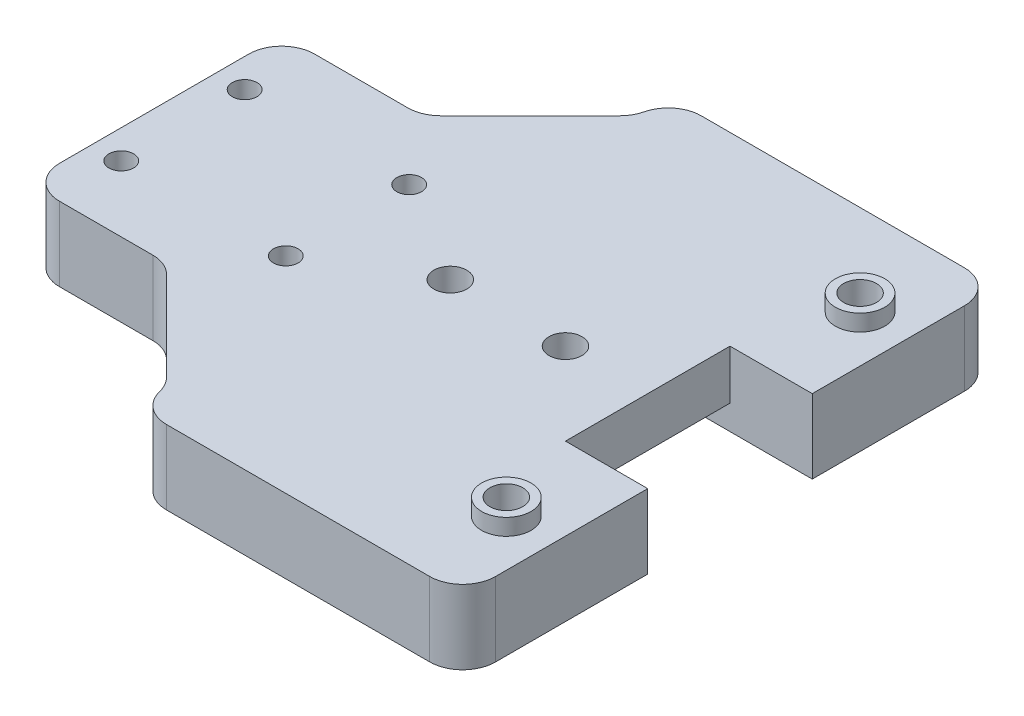
SolidWorks part; units mm, degrees
ref_plane "Front Plane" through (0, 0, 0) normal (0, 0, 1) x (1, 0, 0)
ref_plane "Top Plane" through (0, 0, 0) normal (0, 1, 0) x (1, 0, 0)
ref_plane "Right Plane" through (0, 0, 0) normal (1, 0, 0) x (0, 0, -1)
sketch "Sketch1" plane through (0, 0, 0) normal (0, 1, 0) x (1, 0, 0)
  line L0 (0, 0) -> (21.5, 0) construction
  line L5 (21.5, 20) -> (21.5, -20)
  line L6 (21.5, -20) -> (-20.5, -32.5)
  line L7 (-20.5, -32.5) -> (-84.5, -32.5)
  line L8 (-84.5, -32.5) -> (-84.5, 32.5)
  line L11 (-84.5, 32.5) -> (-20.5, 32.5)
  line L12 (-20.5, 32.5) -> (21.5, 20)
  circle A0 centre (0, 0) radius 12
  point P7 (21.5, 0)
  dimension "D4" = 24
  dimension "D6" = 9.5
  dimension "D1" = 40
  dimension "D2" = 106
  dimension "D3" = 65
  dimension "D5" = 64
extrude "Boss-Extrude1" add sketch "Sketch1" along normal mid plane 9
sketch "Sketch2" plane through (0, 4.5, 0) normal (0, 1, 0) x (1, 0, 0)
  line L0 (0, 0) -> (-19.5, 0) construction
  line L1 (-15.5, -15.5) -> (15.5, -15.5) construction
  line L2 (-15.5, -15.5) -> (-15.5, 15.5) construction
  line L3 (-15.5, 15.5) -> (15.5, 15.5) construction
  line L4 (15.5, -15.5) -> (15.5, 15.5) construction
  line L5 (-15.5, -15.5) -> (15.5, 15.5) construction
  line L6 (-15.5, 15.5) -> (15.5, -15.5) construction
  line L7 (-19.5, 27.5) -> (-19.5, -27.5) construction
  line L9 (-84.5, 32.5) -> (-84.5, -32.5) construction
  circle A0 centre (15.5, 15.5) radius 1.7
  circle A1 centre (-15.5, 15.5) radius 1.7
  circle A2 centre (-15.5, -15.5) radius 1.7
  circle A3 centre (15.5, -15.5) radius 1.7
  circle A4 centre (-19.5, 27.5) radius 1.7
  circle A5 centre (-19.5, -27.5) radius 1.7
  point P0 (0, 0)
  dimension "D2" = 3.4
  dimension "D1" = 31
  dimension "D3" = 55
  dimension "D4" = 65
extrude "Cut-Extrude1" cut sketch "Sketch2" against normal through all
sketch "Sketch4" plane through (0, 4.5, 0) normal (0, 1, 0) x (1, 0, 0)
  line L0 (-64.5, 32.5) -> (-64.5, 22.5)
  line L1 (-20.5, 32.5) -> (-84.5, 32.5) construction
  line L2 (-64.5, 22.5) -> (-51.5, 22.5)
  line L3 (-51.5, 22.5) -> (-51.5, 24.25)
  line L4 (-51.5, 24.25) -> (-62.75, 24.25)
  line L5 (-62.75, 24.25) -> (-62.75, 32.5)
  line L6 (-62.75, 32.5) -> (-64.5, 32.5)
  line L7 (-84.5, 32.5) -> (-84.5, -32.5) construction
  line L8 (0, 0) -> (-84.5, 0) construction
  line L9 (-62.75, -24.25) -> (-62.75, -32.5)
  line L10 (-51.5, -24.25) -> (-62.75, -24.25)
  line L11 (-51.5, -22.5) -> (-51.5, -24.25)
  line L12 (-64.5, -22.5) -> (-51.5, -22.5)
  line L13 (-64.5, -32.5) -> (-64.5, -22.5)
  line L14 (-62.75, -32.5) -> (-64.5, -32.5)
  dimension "D1" = 1.75
  dimension "D2" = 10
  dimension "D3" = 13
  dimension "D4" = 20
extrude "Cut-Extrude3" [suppressed] cut sketch "Sketch4" against normal through all
fillet "Fillet1" radius 4 6 edges at (-84.5, 0, -32.5) (-84.5, 0, 32.5) (-20.5, 0, 32.5) (21.5, 0, 20) (-20.5, 0, -32.5) (21.5, 0, -20)
fillet "Fillet2" [suppressed] radius 0.5
sketch "Sketch5" plane through (0, 4.5, 0) normal (0, 1, 0) x (1, 0, 0)
  line L0 (-24.5, 32.5) -> (-24.5, 10)
  line L1 (-21.0826, 32.5) -> (-80.5, 32.5) construction
  line L2 (-80.5, -32.5) -> (-21.0826, -32.5) construction
  line L3 (-84.5, 28.5) -> (-84.5, -28.5) construction
  line L4 (-24.5, 32.5) -> (26.912, 32.5)
  line L5 (-24.5, -10) -> (-29.5, -10) construction
  line L6 (-24.5, -10) -> (-24.5, 10) construction
  line L7 (-24.5, 10) -> (-29.5, 10) construction
  line L8 (-29.5, -10) -> (-29.5, 10) construction
  line L9 (26.912, 32.5) -> (26.912, -32.5)
  line L11 (-24.5, -32.5) -> (26.912, -32.5)
  line L12 (-24.5, 10) -> (-24.5, -10) construction
  line L13 (-24.5, -10) -> (-24.5, -32.5)
  line L14 (-29.5, 0) -> (0, 0) construction
  line L15 (-24.5, 10) -> (-24.5, -10)
  dimension "D1" = 60
  dimension "D2" = 20
  dimension "D3" = 5
extrude "Cut-Extrude4" cut sketch "Sketch5" against normal through all
fillet "Fillet4" [suppressed] radius 2
sketch "Sketch6" plane through (0, -4.5, 0) normal (0, -1, 0) x (1, 0, 0)
  line L0 (-81, -7.5) -> (-81, 7.5) construction
  line L2 (-24.5, -32.5) -> (-80.5, -32.5) construction
  line L3 (-81, -7.5) -> (-61, -7.5) construction
  line L4 (-61, -7.5) -> (-61, 7.5) construction
  line L5 (-61, 7.5) -> (-81, 7.5) construction
  line L6 (-84.5, -28.5) -> (-84.5, 28.5) construction
  circle A0 centre (-81, -7.5) radius 1.5
  circle A1 centre (-81, 7.5) radius 1.5
  circle A2 centre (-61, -7.5) radius 1.5
  circle A3 centre (-61, 7.5) radius 1.5
  dimension "D3" = 20
  dimension "D5" = 3
  dimension "D1" = 15
  dimension "D2" = 3.5
  dimension "D4" = 25
extrude "Cut-Extrude5" cut sketch "Sketch6" against normal blind 41
sketch "Sketch7" plane through (0, 4.5, 0) normal (0, 1, 0) x (1, 0, 0)
  line L0 (-24.5, 32.5) -> (-24.5, -32.5) construction
  line L1 (-24.5, 10) -> (-54.5, 10)
  line L2 (-24.5, 10) -> (-24.5, -10)
  line L3 (-24.5, -10) -> (-54.5, -10)
  line L4 (-54.5, 10) -> (-54.5, -10)
  line L5 (-80.5, -32.5) -> (-24.5, -32.5) construction
  dimension "D1" = 20
  dimension "D2" = 30
  dimension "D3" = 22.5
extrude "Cut-Extrude6" cut sketch "Sketch7" against normal blind 3 from offset 6 offset against normal yes
sketch "Sketch8" plane through (0, 4.5, 0) normal (0, 1, 0) x (1, 0, 0)
  line L0 (-84.5, 28.5) -> (-84.5, -28.5) construction
  line L1 (-84.5, 15.5) -> (-54.5, 15.5)
  line L2 (-84.5, 15.5) -> (-84.5, 32.5)
  line L3 (-84.5, 32.5) -> (-54.5, 32.5)
  line L4 (-54.5, 15.5) -> (-54.5, 32.5)
  line L5 (-24.5, 32.5) -> (-24.5, -32.5) construction
  line L6 (-24.5, 32.5) -> (-80.5, 32.5) construction
  line L7 (-84.5, 0) -> (-24.5, 0) construction
  line L9 (-84.5, -32.5) -> (-54.5, -32.5)
  line L10 (-54.5, -15.5) -> (-54.5, -32.5)
  line L11 (-84.5, -15.5) -> (-54.5, -15.5)
  line L12 (-84.5, -15.5) -> (-84.5, -32.5)
  point P6 (0, 0)
  point P7 (-24.5, 0)
  dimension "D1" = 17
  dimension "D2" = 30
extrude "Cut-Extrude7" cut sketch "Sketch8" against normal blind 9
fillet "Fillet5" radius 4 4 edges at (-84.5, 0, -15.5) (-84.5, 0, 15.5) (-54.5, 0, -32.5) (-54.5, 0, 32.5)
sketch "Sketch10" plane through (0, 4.5, 0) normal (0, 1, 0) x (1, 0, 0)
  line L0 (-24.5, 32.5) -> (-24.5, -32.5) construction
  line L1 (-24.5, -32.5) -> (-14.5, -32.5)
  line L2 (-24.5, -32.5) -> (-24.5, -10)
  line L3 (-24.5, -10) -> (-14.5, -10)
  line L4 (-14.5, -32.5) -> (-14.5, -10)
  line L5 (-50.5, -32.5) -> (-24.5, -32.5) construction
  line L6 (-24.5, 32.5) -> (-14.5, 32.5)
  line L7 (-24.5, 32.5) -> (-24.5, 10)
  line L8 (-24.5, 10) -> (-14.5, 10)
  line L9 (-14.5, 32.5) -> (-14.5, 10)
  line L10 (-54.5, -10) -> (-24.5, -10) construction
  line L11 (-24.5, 32.5) -> (-24.5, -32.5) construction
  line L12 (-24.5, 32.5) -> (-50.5, 32.5) construction
  dimension "D1" = 10
extrude "Boss-Extrude2" add sketch "Sketch10" against normal blind 9
sketch "Sketch13" plane through (0, 4.5, 0) normal (0, 1, 0) x (1, 0, 0)
  line L0 (-50.5, -32.5) -> (-14.5, -32.5) construction
  line L1 (-14.5, -32.5) -> (-14.5, -10) construction
  line L2 (-24.5, 0) -> (-84.5, 0) construction
  line L3 (-24.5, 10) -> (-24.5, -10) construction
  line L4 (-84.5, 11.5) -> (-84.5, -11.5) construction
  circle A0 centre (-20.19, -21.5) radius 3
  circle A1 centre (-20.19, 21.5) radius 3
  dimension "D1" = 6
  dimension "D2" = 11
  dimension "D3" = 5.69
extrude "Boss-Extrude4" add sketch "Sketch13" along normal blind 2
sketch "Sketch11" plane through (0, 4.5, 0) normal (0, 1, 0) x (1, 0, 0)
  line L0 (-50.5, -32.5) -> (-14.5, -32.5) construction
  line L1 (-14.5, -32.5) -> (-14.5, -10) construction
  line L2 (-84.5, 0) -> (-24.5, 0) construction
  line L3 (-84.5, 11.5) -> (-84.5, -11.5) construction
  line L4 (-24.5, 10) -> (-24.5, -10) construction
  circle A0 centre (-20.19, -21.5) radius 2
  circle A1 centre (-20.19, 21.5) radius 2
  dimension "D1" = 4
  dimension "D2" = 11
  dimension "D3" = 5.69
extrude "Cut-Extrude8" cut sketch "Sketch11" against normal blind 9 and the other way blind 5
fillet "Fillet6" radius 4 2 edges at (-14.5, 0, -32.5) (-14.5, 0, 32.5)
sketch "Sketch12" plane through (0, 4.5, 0) normal (0, 1, 0) x (1, 0, 0)
  line L0 (-54.5, 28.5) -> (-67.5, 15.5)
  line L1 (-54.5, 15.5) -> (-54.5, 28.5) construction
  line L2 (-80.5, 15.5) -> (-54.5, 15.5) construction
  line L3 (-67.5, 15.5) -> (-54.5, 15.5)
  line L4 (-54.5, 15.5) -> (-54.5, 28.5)
  line L5 (-54.5, -28.5) -> (-67.5, -15.5)
  line L6 (-54.5, -28.5) -> (-54.5, -15.5) construction
  line L7 (-54.5, -15.5) -> (-80.5, -15.5) construction
  line L8 (-67.5, -15.5) -> (-54.5, -15.5)
  line L9 (-54.5, -15.5) -> (-54.5, -28.5)
  arc A0 (-50.5, 32.5) -> (-54.5, 28.5) centre (-50.5, 28.5) ccw construction
  arc A1 (-54.5, -28.5) -> (-50.5, -32.5) centre (-50.5, -28.5) ccw construction
extrude "Boss-Extrude3" add sketch "Sketch12" against normal blind 9
fillet "Fillet8" radius 4 4 edges at (-54.5, 0, 28.5) (-67.5, 0, 15.5) (-67.5, 0, -15.5) (-54.5, 0, -28.5)
sketch "Sketch14" plane through (0, -1.5, 0) normal (0, -1, 0) x (1, 0, 0)
  line L0 (-24.5, 0) -> (-84.5, 0) construction
  line L1 (-24.5, 10) -> (-24.5, -10) construction
  line L2 (-84.5, -11.5) -> (-84.5, 11.5) construction
  line L3 (-54.5, -10) -> (-54.5, 10) construction
  circle A0 centre (-48.5, 0) radius 2
  circle A1 centre (-34.5, 0) radius 2
  dimension "D2" = 14
  dimension "D3" = 4
  dimension "D1" = 6
extrude "Cut-Extrude9" cut sketch "Sketch14" against normal blind 16
